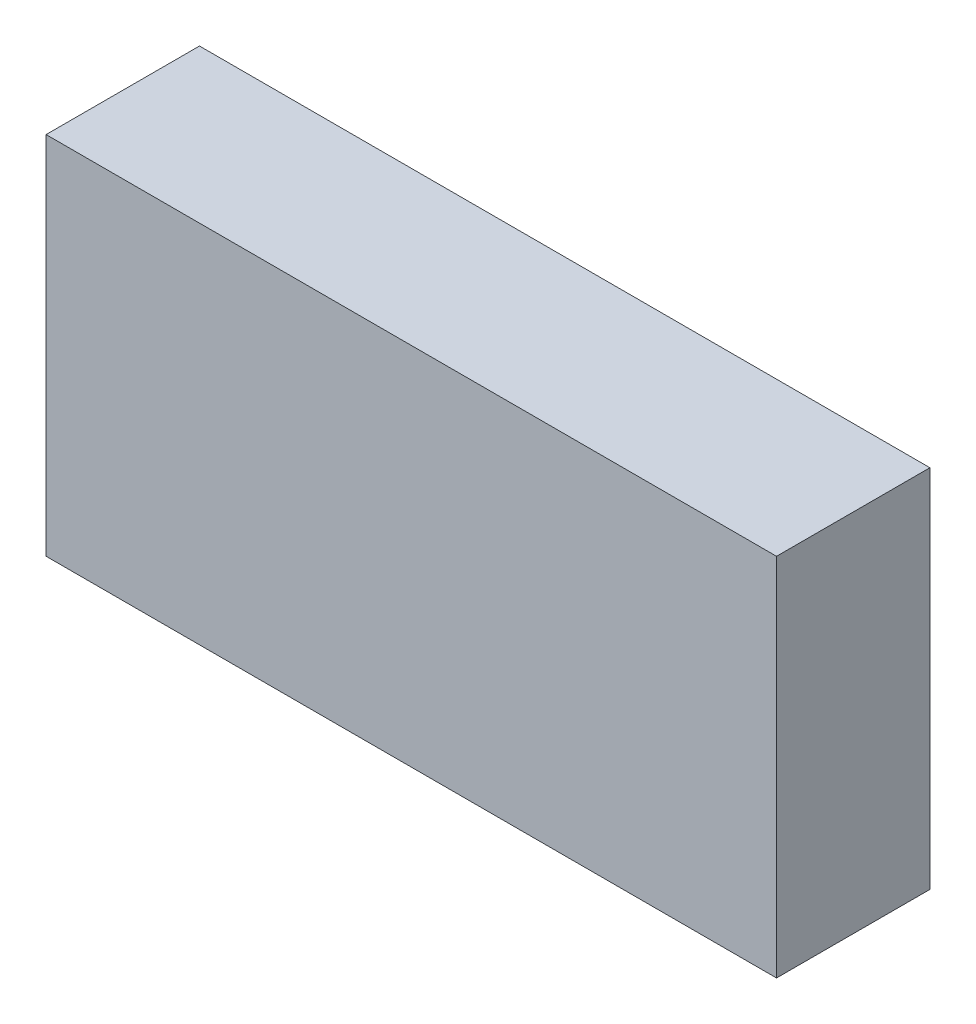
SolidWorks part; units mm, degrees
ref_plane "Front Plane" through (0, 0, 0) normal (0, 0, 1) x (1, 0, 0)
ref_plane "Top Plane" through (0, 0, 0) normal (0, 1, 0) x (1, 0, 0)
ref_plane "Right Plane" through (0, 0, 0) normal (1, 0, 0) x (0, 0, -1)
sketch "Sketch1" plane through (0, 0, 0) normal (0, 0, 1) x (1, 0, 0)
  line L1 (0, 0) -> (25.4, 0)
  line L2 (0, 0) -> (0, -12.7)
  line L3 (0, -12.7) -> (25.4, -12.7)
  line L4 (25.4, 0) -> (25.4, -12.7)
  dimension "D1" = 25.4
  dimension "D2" = 12.7
extrude "Boss-Extrude1" add sketch "Sketch1" along normal blind 5.334
